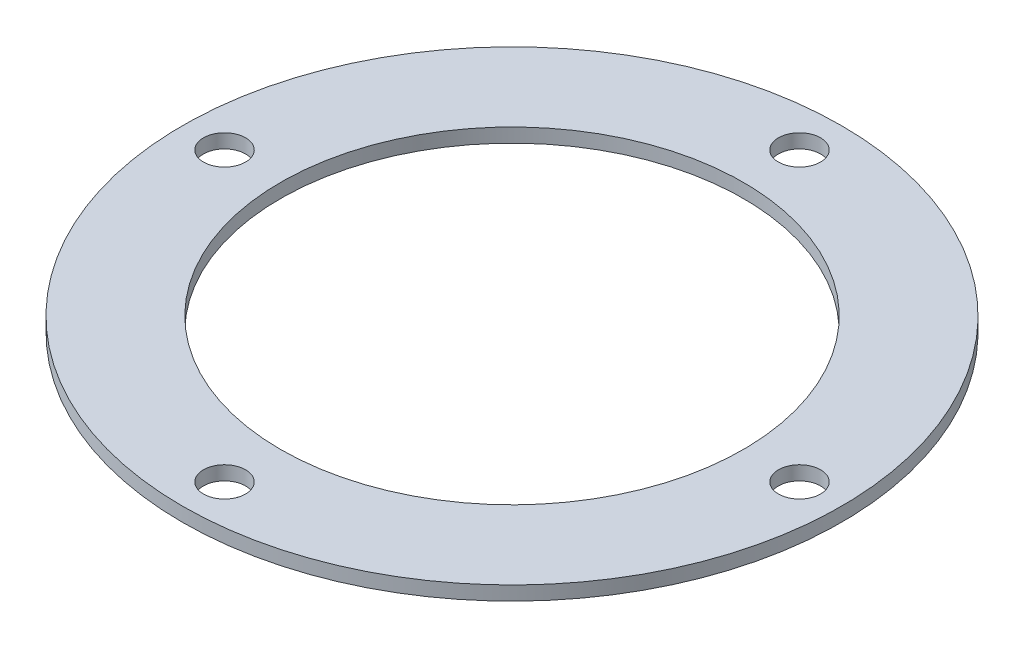
SolidWorks part; units mm, degrees
material "A-玻璃纤维"
ref_plane "前视基准面" through (0, 0, 0) normal (0, 0, 1) x (1, 0, 0)
ref_plane "上视基准面" through (0, 0, 0) normal (0, 1, 0) x (1, 0, 0)
ref_plane "右视基准面" through (0, 0, 0) normal (1, 0, 0) x (0, 0, -1)
other "Configuration Table"
sketch "草图1" plane through (0, 0, 0) normal (0, 1, 0) x (1, 0, 0)
  circle A0 centre (0, 0) radius 16.5
  circle A1 centre (0, 0) radius 23.5
  dimension "D1" = 47
  dimension "D2" = 33
extrude "凸台-拉伸1" add sketch "草图1" along normal blind 1
sketch "草图2" plane through (0, 1, 0) normal (0, 1, 0) x (1, 0, 0)
  circle A0 centre (0, 0) radius 20.5 construction
  circle A1 centre (0, 0) radius 23.5 construction
  circle A2 centre (20.5, 0) radius 1.5
  circle A3 centre (0, -20.5) radius 1.5
  circle A4 centre (-20.5, 0) radius 1.5
  circle A5 centre (0, 20.5) radius 1.5
  dimension "D1" = 3
  dimension "D2" = 3
  dimension "D3" = 4
extrude "切除-拉伸1" cut sketch "草图2" against normal blind 1
